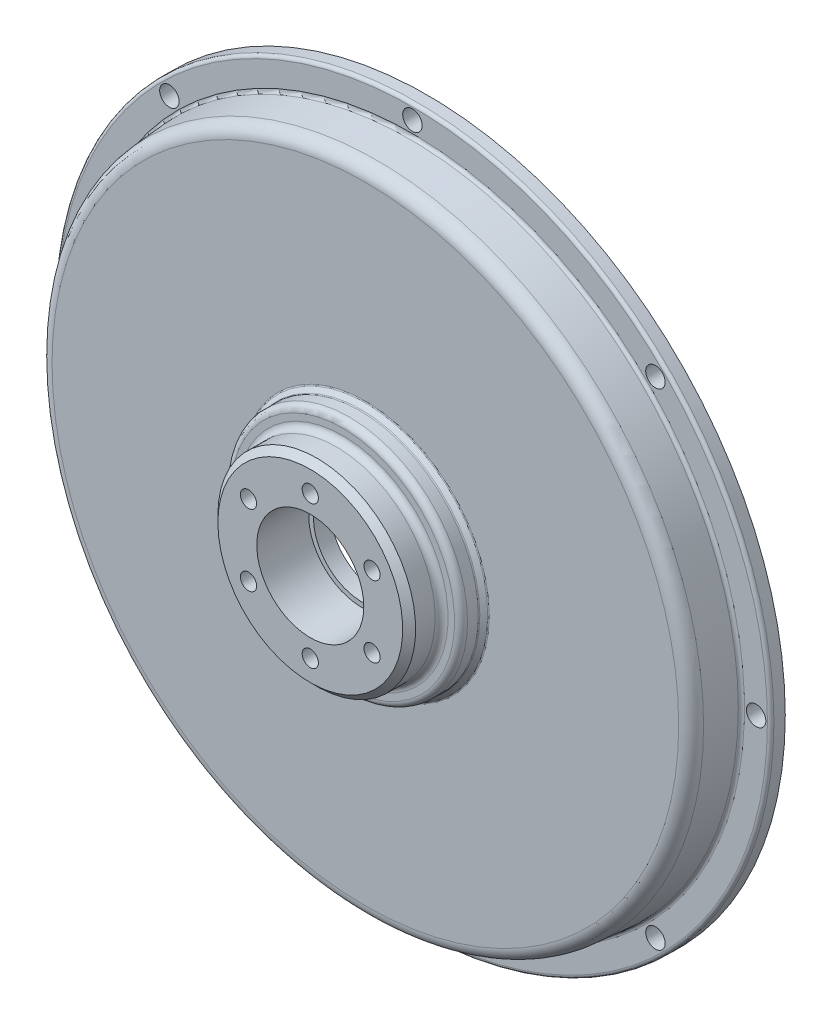
SolidWorks part; units mm, degrees
material "1060 Сплав"
ref_plane "Спереди" through (0, 0, 0) normal (0, 0, 1) x (1, 0, 0)
ref_plane "Сверху" through (0, 0, 0) normal (0, 1, 0) x (1, 0, 0)
ref_plane "Справа" through (0, 0, 0) normal (1, 0, 0) x (0, 0, -1)
sketch "Эскиз1" plane through (0, 0, 0) normal (0, 1, 0) x (1, 0, 0)
  line L0 (0, 0) -> (-110.5, 0) construction
  line L1 (-110.5, 0) -> (-110.5, -3.5)
  line L2 (-109.5, -4.5) -> (-102.4224, -4.5)
  line L3 (-101.5, -4.5) -> (-101.5, -19) construction
  line L4 (-101.5, -19) -> (-36.5, -19) construction
  line L5 (-110.5, 0) -> (0, 0)
  line L6 (-36.5, -19) -> (-36.5, -36) construction
  line L7 (-36.5, -36) -> (0, -36) construction
  line L8 (0, 0) -> (0, -36) construction
  line L9 (-36.5, -20.5) -> (-36.5, -24)
  line L10 (-34.5, -26) -> (-32.5, -26)
  line L11 (-30.5, -28) -> (-30.5, -34)
  line L12 (-28.5, -36) -> (0, -36)
  line L13 (-101.4257, -5.4194) -> (-100.6249, -15.3224)
  line L14 (-96.6379, -19) -> (-38, -19)
  line L15 (-38, -19) -> (-36.5, -20.5)
  line L16 (-30.5, -34) -> (-28.5, -36)
  line L17 (0, 0) -> (0, -36)
  arc A0 (-100.6249, -15.3224) -> (-96.6379, -19) centre (-96.6379, -15) ccw
  arc A1 (-102.4224, -4.5) -> (-101.4257, -5.4194) centre (-102.4224, -5.5) cw
  arc A2 (-32.5, -26) -> (-30.5, -28) centre (-32.5, -28) cw
  arc A3 (-36.5, -24) -> (-34.5, -26) centre (-34.5, -24) ccw
  arc A4 (-110.5, -3.5) -> (-109.5, -4.5) centre (-109.5, -3.5) ccw
  point P12 (-30.5, -36)
  point P15 (-100.3276, -19)
  point P25 (-36.5, -26)
  point P30 (-110.5, -4.5)
  dimension "D8" = 4
  dimension "D9" = 1
  dimension "D10" = 2
  dimension "D11" = 1
  dimension "D1" = 110.5
  dimension "D2" = 36.5
  dimension "D3" = 14.5
  dimension "D4" = 9
  dimension "D5" = 4.5
  dimension "D6" = 17
  dimension "D7" = 30.5
revolve "Повернуть1" add sketch "Эскиз1" angle 360 about L17
fillet "Скругление1" radius 0.5 2 edges at (-38, 0, 19) (-36.5, 0, 20.5)
sketch "Эскиз2" plane through (0, 0, 4.5) normal (0, 0, 1) x (1, 0, 0)
  circle A0 centre (0, 0) radius 106 construction
  circle A1 centre (0, 106) radius 3
  circle A2 centre (74.9533, 74.9533) radius 3
  circle A3 centre (106, 0) radius 3
  circle A4 centre (74.9533, -74.9533) radius 3
  circle A5 centre (0, -106) radius 3
  circle A6 centre (-74.9533, -74.9533) radius 3
  circle A7 centre (-106, 0) radius 3
  circle A8 centre (-74.9533, 74.9533) radius 3
  point P22 (0, 0)
  dimension "D1" = 212
  dimension "D2" = 6
  dimension "D3" = 8
extrude "Вырез-Вытянуть1" cut sketch "Эскиз2" against normal blind 10
sketch "Эскиз3" plane through (0, 0, 36) normal (0, 0, 1) x (1, 0, 0)
  circle A0 centre (0, 0) radius 16.5
  dimension "D1" = 33
extrude "Вырез-Вытянуть2" cut sketch "Эскиз3" against normal blind 16
sketch "Эскиз4" plane through (0, 0, 36) normal (0, 0, 1) x (1, 0, 0)
  circle A0 centre (0, 0) radius 22 construction
  circle A1 centre (0, 22) radius 2.5
  circle A2 centre (19.0526, 11) radius 2.5
  circle A3 centre (19.0526, -11) radius 2.5
  circle A4 centre (0, -22) radius 2.5
  circle A5 centre (-19.0526, -11) radius 2.5
  circle A6 centre (-19.0526, 11) radius 2.5
  point P18 (0, 0)
  dimension "D1" = 44
  dimension "D2" = 5
  dimension "D3" = 6
extrude "Вырез-Вытянуть3" cut sketch "Эскиз4" against normal blind 15
sketch "Эскиз5" plane through (0, 0, 0) normal (0, 0, -1) x (-1, 0, 0)
  circle A0 centre (0, 0) radius 95
  dimension "D1" = 190
extrude "Вырез-Вытянуть4" cut sketch "Эскиз5" against normal blind 15
sketch "Эскиз6" plane through (0, 0, 20) normal (0, 0, 1) x (1, 0, 0)
  circle A0 centre (0, 0) radius 15
  dimension "D1" = 30
extrude "Вырез-Вытянуть5" cut sketch "Эскиз6" against normal blind 15
